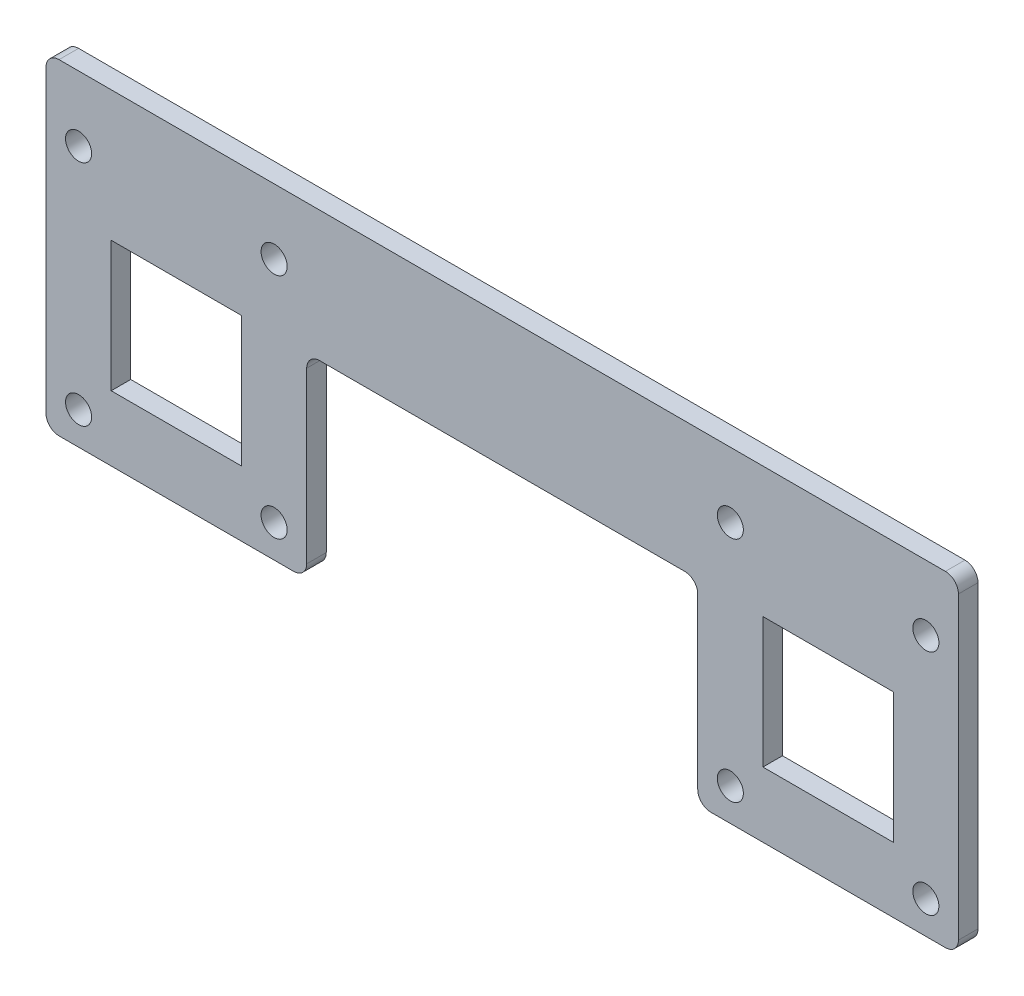
SolidWorks part; units mm, degrees
ref_plane "前视基准面" through (0, 0, 0) normal (0, 0, 1) x (1, 0, 0)
ref_plane "上视基准面" through (0, 0, 0) normal (0, 1, 0) x (1, 0, 0)
ref_plane "右视基准面" through (0, 0, 0) normal (1, 0, 0) x (0, 0, -1)
sketch "草图1" plane through (0, 0, 0) normal (0, 0, 1) x (1, 0, 0)
  line L1 (-70, 25) -> (70, 25)
  line L2 (-70, 25) -> (-70, -25)
  line L3 (-70, -25) -> (70, -25)
  line L4 (70, 25) -> (70, -25)
  line L5 (-70, 25) -> (70, -25) construction
  line L6 (-70, -25) -> (70, 25) construction
  point P0 (0, 0)
  dimension "D1" = 140
  dimension "D2" = 50
extrude "凸台-拉伸1" add sketch "草图1" along normal blind 3
sketch "草图2" plane through (0, 0, 3) normal (0, 0, 1) x (1, 0, 0)
  line L0 (70, 25) -> (-70, 25) construction
  line L1 (-60, 5) -> (-40, 5)
  line L2 (-60, 5) -> (-60, -15)
  line L3 (-60, -15) -> (-40, -15)
  line L4 (-40, 5) -> (-40, -15)
  line L5 (-60, 5) -> (-40, -15) construction
  line L6 (-60, -15) -> (-40, 5) construction
  line L7 (-70, 25) -> (-70, -25) construction
  line L8 (0, -55) -> (0, 55) construction
  line L9 (60, -15) -> (40, -15)
  line L10 (40, 5) -> (40, -15)
  line L11 (60, 5) -> (40, 5)
  line L12 (60, 5) -> (60, -15)
  point P0 (-50, -5)
  dimension "D1" = 20
  dimension "D2" = 20
  dimension "D3" = 20
  dimension "D4" = 10
extrude "切除-拉伸1" cut sketch "草图2" against normal blind 3
sketch "草图3" plane through (0, 0, 3) normal (0, 0, 1) x (1, 0, 0)
  line L0 (0, -1.65) -> (0, 1.65) construction
  line L1 (-30, 5) -> (30, 5)
  line L2 (-30, 5) -> (-30, -25)
  line L3 (-30, -25) -> (30, -25)
  line L4 (30, 5) -> (30, -25)
  line L5 (-30, 5) -> (30, -25) construction
  line L6 (-30, -25) -> (30, 5) construction
  line L7 (70, 25) -> (-70, 25) construction
  point P0 (0, -10)
  dimension "D1" = 60
  dimension "D2" = 30
  dimension "D3" = 20
extrude "切除-拉伸2" cut sketch "草图3" against normal blind 3
sketch "草图4" plane through (0, 0, 3) normal (0, 0, 1) x (1, 0, 0)
  line L0 (-60, -15) -> (-70, -25) construction
  line L1 (-40, -15) -> (-30, -25) construction
  line L2 (0, -1.65) -> (0, 1.65) construction
  line L3 (-60, 5) -> (-60, -15) construction
  line L4 (40, 5) -> (40, -15) construction
  line L5 (-60, -5) -> (40, -5) construction
  circle A0 centre (-65, -20) radius 2
  circle A1 centre (-35, -20) radius 2
  circle A2 centre (65, -20) radius 2
  circle A3 centre (35, -20) radius 2
extrude "切除-拉伸4" cut sketch "草图4" against normal blind 3
sketch "草图5" plane through (0, 0, 3) normal (0, 0, 1) x (1, 0, 0)
  line L0 (70, 25) -> (-70, 25) construction
  line L2 (-70, 25) -> (-70, -25) construction
  line L3 (0, -1.65) -> (0, 1.65) construction
  circle A0 centre (-65, 15) radius 2
  circle A1 centre (-35, 15) radius 2
  circle A2 centre (35, 15) radius 2
  circle A3 centre (65, 15) radius 2
  dimension "D1" = 4
  dimension "D4" = 30
  dimension "D2" = 10
  dimension "D3" = 5
extrude "切除-拉伸5" cut sketch "草图5" against normal blind 3
fillet "圆角1" radius 2 8 edges at (70, 25, 1.5) (70, -25, 1.5) (30, -25, 1.5) (30, 5, 1.5) (-30, 5, 1.5) (-30, -25, 1.5) (-70, -25, 1.5) (-70, 25, 1.5)
